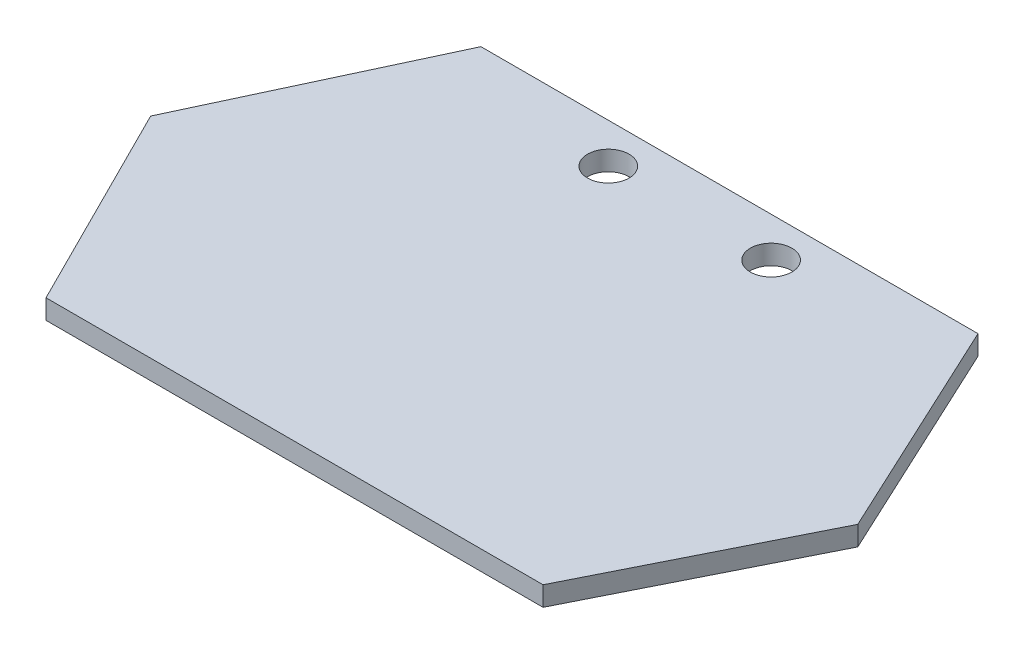
SolidWorks part; units mm, degrees
ref_plane "Front Plane" through (0, 0, 0) normal (0, 0, 1) x (1, 0, 0)
ref_plane "Top Plane" through (0, 0, 0) normal (0, 1, 0) x (1, 0, 0)
ref_plane "Right Plane" through (0, 0, 0) normal (1, 0, 0) x (0, 0, -1)
sketch "Sketch1" plane through (0, 0, 0) normal (0, 1, 0) x (1, 0, 0)
  line L0 (-12.3278, 14.6538) -> (13.0722, 14.6538)
  line L1 (13.0722, 14.6538) -> (18.4394, 3.1437)
  line L2 (18.4394, 3.1437) -> (13.0722, -7.5712)
  line L3 (13.0722, -7.5712) -> (0.3722, -7.5712)
  line L4 (0.3722, -7.5712) -> (-12.3278, -7.5712)
  line L5 (-12.3278, -7.5712) -> (-17.6951, 3.1437)
  line L6 (-17.6951, 3.1437) -> (-12.3278, 14.6538)
  circle A0 centre (-3.7871, 12.6218) radius 1.0604
  circle A1 centre (4.5314, 12.6218) radius 1.0604
  dimension "D9" = 2.1209
  dimension "D10" = 2.1209
  dimension "D1" = 25.4
  dimension "D2" = 22.225
  dimension "D3" = 115
  dimension "D4" = 12.7
  dimension "D5" = 12.7
  dimension "D6" = 12.7
  dimension "D7" = 12.7
  dimension "D8" = 115
  dimension "D11" = 8.3185
  dimension "D12" = 4.1593
  dimension "D13" = 4.1593
  dimension "D14" = 2.032
  dimension "D15" = 12.7
  dimension "D16" = 12.7
  dimension "D17" = 11.984
  dimension "D18" = 11.984
extrude "Boss-Extrude1" add sketch "Sketch1" along normal blind 1
